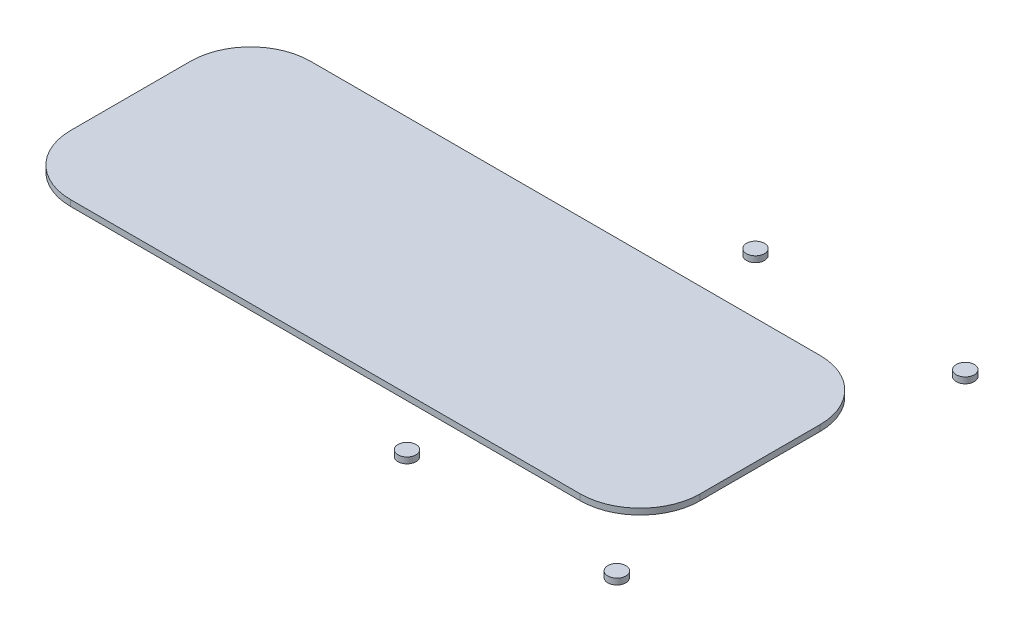
SolidWorks part; units mm, degrees
ref_plane "Front Plane" through (0, 0, 0) normal (0, 0, 1) x (1, 0, 0)
ref_plane "Top Plane" through (0, 0, 0) normal (0, 1, 0) x (1, 0, 0)
ref_plane "Right Plane" through (0, 0, 0) normal (1, 0, 0) x (0, 0, -1)
sketch "Sketch1" plane through (0, 0, 0) normal (0, 1, 0) x (1, 0, 0)
  line L1 (0, 0) -> (266.7, 0)
  line L2 (0, 0) -> (0, 101.6)
  line L3 (0, 101.6) -> (266.7, 101.6)
  line L4 (266.7, 0) -> (266.7, 101.6)
  dimension "D1" = 266.7
  dimension "D2" = 101.6
extrude "Boss-Extrude1" add sketch "Sketch1" along normal blind 2.54
sketch "Sketch3" plane through (0, 2.54, 0) normal (0, 1, 0) x (1, 0, 0)
  line L0 (0, 50.8) -> (266.7, 50.8) construction
  line L1 (0, 101.6) -> (0, 0) construction
  line L2 (266.7, 0) -> (266.7, 101.6) construction
  line L4 (190.9173, 124.6188) -> (279.8173, 124.6188) construction
  line L5 (190.9173, 124.6188) -> (190.9173, -23.0187) construction
  line L6 (190.9173, -23.0187) -> (279.8173, -23.0187) construction
  line L7 (279.8173, 124.6188) -> (279.8173, -23.0187) construction
  line L8 (190.9173, 124.6188) -> (279.8173, -23.0187) construction
  line L9 (190.9173, -23.0187) -> (279.8173, 124.6188) construction
  circle A0 centre (190.9173, 124.6188) radius 3.81
  circle A1 centre (279.8173, 124.6188) radius 3.81
  circle A2 centre (279.8173, -23.0187) radius 3.81
  circle A3 centre (190.9173, -23.0187) radius 3.81
  point P6 (235.3673, 50.8)
  point P15 (239.5598, 50.8)
  point P16 (235.3673, 50.8)
  dimension "D3" = 7.62
  dimension "D1" = 147.6375
  dimension "D2" = 88.9
extrude "Boss-Extrude2" add sketch "Sketch3" along normal blind 2.54 separate body
fillet "Fillet1" radius 25.4 4 edges at (0, 1.27, -101.6) (0, 1.27, 0) (266.7, 1.27, 0) (266.7, 1.27, -101.6)
